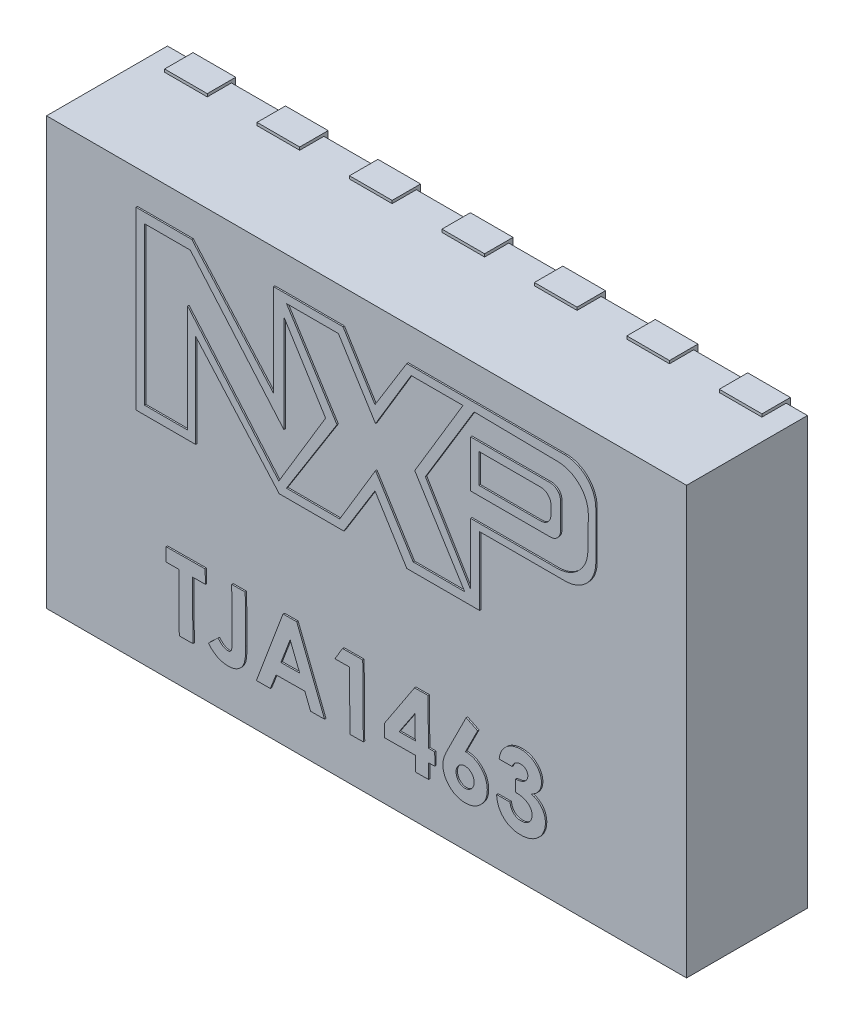
SolidWorks part; units mm, degrees
ref_plane "Front Plane" through (0, 0, 0) normal (0, 0, 1) x (1, 0, 0)
ref_plane "Top Plane" through (0, 0, 0) normal (0, 1, 0) x (1, 0, 0)
ref_plane "Right Plane" through (0, 0, 0) normal (1, 0, 0) x (0, 0, -1)
sketch "Sketch1" plane through (0, 0, 0) normal (0, 0, 1) x (1, 0, 0)
  line L1 (2.25, 1.5) -> (-2.25, 1.5)
  line L2 (2.25, 1.5) -> (2.25, -1.5)
  line L3 (2.25, -1.5) -> (-2.25, -1.5)
  line L4 (-2.25, 1.5) -> (-2.25, -1.5)
  line L5 (2.25, 1.5) -> (-2.25, -1.5) construction
  line L6 (2.25, -1.5) -> (-2.25, 1.5) construction
  point P0 (0, 0)
  dimension "D1" = 4.5
  dimension "D2" = 3
extrude "Boss-Extrude1" add sketch "Sketch1" along normal blind 0.85
sketch "Sketch2" plane through (0, 0, 0) normal (0, 0, -1) x (-1, 0, 0)
  line L0 (-2.25, 1.5) -> (2.25, 1.5) construction
  line L1 (2.1, 0.8) -> (-2.1, 0.8)
  line L2 (2.1, 0.8) -> (2.1, -0.8)
  line L3 (2.1, -0.8) -> (-2.1, -0.8)
  line L4 (-2.1, 0.8) -> (-2.1, -0.8)
  line L5 (2.1, 0.8) -> (-2.1, -0.8) construction
  line L6 (2.1, -0.8) -> (-2.1, 0.8) construction
  line L7 (-2.1, 1.6573) -> (-1.8, 1.6573)
  line L8 (-2.1, 1.6573) -> (-2.1, 1.1)
  line L9 (-2.1, 1.1) -> (-1.8, 1.1)
  line L10 (-1.8, 1.6573) -> (-1.8, 1.1)
  line L11 (-1.45, 1.6573) -> (-1.45, 1.1)
  line L12 (-1.45, 1.6573) -> (-1.15, 1.6573)
  line L13 (-1.15, 1.6573) -> (-1.15, 1.1)
  line L14 (-1.45, 1.1) -> (-1.15, 1.1)
  line L15 (-0.8, 1.6573) -> (-0.8, 1.1)
  line L16 (-0.8, 1.6573) -> (-0.5, 1.6573)
  line L17 (-0.5, 1.6573) -> (-0.5, 1.1)
  line L18 (-0.8, 1.1) -> (-0.5, 1.1)
  line L19 (-0.15, 1.6573) -> (-0.15, 1.1)
  line L20 (-0.15, 1.6573) -> (0.15, 1.6573)
  line L21 (0.15, 1.6573) -> (0.15, 1.1)
  line L22 (-0.15, 1.1) -> (0.15, 1.1)
  line L23 (0.5, 1.6573) -> (0.5, 1.1)
  line L24 (0.5, 1.6573) -> (0.8, 1.6573)
  line L25 (0.8, 1.6573) -> (0.8, 1.1)
  line L26 (0.5, 1.1) -> (0.8, 1.1)
  line L27 (1.15, 1.6573) -> (1.15, 1.1)
  line L28 (1.15, 1.6573) -> (1.45, 1.6573)
  line L29 (1.45, 1.6573) -> (1.45, 1.1)
  line L30 (1.15, 1.1) -> (1.45, 1.1)
  line L31 (1.8, 1.6573) -> (1.8, 1.1)
  line L32 (1.8, 1.6573) -> (2.1, 1.6573)
  line L33 (2.1, 1.6573) -> (2.1, 1.1)
  line L34 (1.8, 1.1) -> (2.1, 1.1)
  line L35 (0, 0) -> (1.2289, 0) construction
  line L36 (1.8, -1.1) -> (2.1, -1.1)
  line L37 (2.1, -1.6573) -> (2.1, -1.1)
  line L38 (1.8, -1.6573) -> (2.1, -1.6573)
  line L39 (1.8, -1.6573) -> (1.8, -1.1)
  line L40 (1.15, -1.1) -> (1.45, -1.1)
  line L41 (1.45, -1.6573) -> (1.45, -1.1)
  line L42 (1.15, -1.6573) -> (1.45, -1.6573)
  line L43 (1.15, -1.6573) -> (1.15, -1.1)
  line L44 (0.5, -1.1) -> (0.8, -1.1)
  line L45 (0.8, -1.6573) -> (0.8, -1.1)
  line L46 (0.5, -1.6573) -> (0.8, -1.6573)
  line L47 (0.5, -1.6573) -> (0.5, -1.1)
  line L48 (-0.15, -1.1) -> (0.15, -1.1)
  line L49 (0.15, -1.6573) -> (0.15, -1.1)
  line L50 (-0.15, -1.6573) -> (0.15, -1.6573)
  line L51 (-0.15, -1.6573) -> (-0.15, -1.1)
  line L52 (-0.8, -1.1) -> (-0.5, -1.1)
  line L53 (-0.5, -1.6573) -> (-0.5, -1.1)
  line L54 (-0.8, -1.6573) -> (-0.5, -1.6573)
  line L55 (-0.8, -1.6573) -> (-0.8, -1.1)
  line L56 (-1.45, -1.1) -> (-1.15, -1.1)
  line L57 (-1.15, -1.6573) -> (-1.15, -1.1)
  line L58 (-1.45, -1.6573) -> (-1.15, -1.6573)
  line L59 (-1.45, -1.6573) -> (-1.45, -1.1)
  line L60 (-1.8, -1.6573) -> (-1.8, -1.1)
  line L61 (-2.1, -1.1) -> (-1.8, -1.1)
  line L62 (-2.1, -1.6573) -> (-2.1, -1.1)
  line L63 (-2.1, -1.6573) -> (-1.8, -1.6573)
  point P0 (0, 0)
  dimension "D1" = 1.6
  dimension "D2" = 4.2
  dimension "D3" = 0.4
  dimension "D4" = 0.3
  dimension "D5" = 7
extrude "Boss-Extrude2" add sketch "Sketch2" along normal blind 0.03
sketch "Sketch3" plane through (0, 0, 0.85) normal (0, 0, 1) x (1, 0, 0)
  line L1 (-2.25, 1.5) -> (3.2924, 1.5)
  line L2 (-2.25, 1.5) -> (-2.25, 1.9025)
  line L3 (-2.25, 1.9025) -> (3.2924, 1.9025)
  line L4 (3.2924, 1.5) -> (3.2924, 1.9025)
  line L5 (-2.25, -1.5) -> (2.8586, -1.5)
  line L6 (-2.25, -1.5) -> (-2.25, -2.0374)
  line L7 (-2.25, -2.0374) -> (2.8586, -2.0374)
  line L8 (2.8586, -1.5) -> (2.8586, -2.0374)
extrude "Cut-Extrude1" cut sketch "Sketch3" against normal blind 2.03
sketch "Sketch4" plane through (0, -1.5, 0) normal (0, -1, 0) x (1, 0, 0)
  line L0 (-1.8, 0) -> (-1.8, -0.03) construction
  line L1 (-2.1, -0.03) -> (-1.8, -0.03)
  line L2 (-2.1, -0.03) -> (-2.1, 0.17)
  line L3 (-2.1, 0.17) -> (-1.8, 0.17)
  line L4 (-1.8, -0.03) -> (-1.8, 0.17)
  line L5 (-1.45, -0.03) -> (-1.45, 0.17)
  line L6 (-1.45, -0.03) -> (-1.15, -0.03)
  line L7 (-1.15, -0.03) -> (-1.15, 0.17)
  line L8 (-1.45, 0.17) -> (-1.15, 0.17)
  line L9 (-0.8, -0.03) -> (-0.8, 0.17)
  line L10 (-0.8, -0.03) -> (-0.5, -0.03)
  line L11 (-0.5, -0.03) -> (-0.5, 0.17)
  line L12 (-0.8, 0.17) -> (-0.5, 0.17)
  line L13 (-0.15, -0.03) -> (-0.15, 0.17)
  line L14 (-0.15, -0.03) -> (0.15, -0.03)
  line L15 (0.15, -0.03) -> (0.15, 0.17)
  line L16 (-0.15, 0.17) -> (0.15, 0.17)
  line L17 (0.5, -0.03) -> (0.5, 0.17)
  line L18 (0.5, -0.03) -> (0.8, -0.03)
  line L19 (0.8, -0.03) -> (0.8, 0.17)
  line L20 (0.5, 0.17) -> (0.8, 0.17)
  line L21 (1.15, -0.03) -> (1.15, 0.17)
  line L22 (1.15, -0.03) -> (1.45, -0.03)
  line L23 (1.45, -0.03) -> (1.45, 0.17)
  line L24 (1.15, 0.17) -> (1.45, 0.17)
  line L25 (1.8, -0.03) -> (1.8, 0.17)
  line L26 (1.8, -0.03) -> (2.1, -0.03)
  line L27 (2.1, -0.03) -> (2.1, 0.17)
  line L28 (1.8, 0.17) -> (2.1, 0.17)
  dimension "D1" = 0
  dimension "D2" = 0.2
  dimension "D3" = 7
extrude "Boss-Extrude3" add sketch "Sketch4" along normal blind 0.02
mirror "Mirror1" about plane through (0, 0, 0) normal (0, 1, 0) of "Boss-Extrude3"
sketch "Sketch8" plane through (0, 0, 0.85) normal (0, 0, 1) x (1, 0, 0)
  line L0 (70.666, 256.4211) -> (518.666, 256.4211) construction
  line L1 (-1.2186, 1.2679) -> (-0.6447, 0.6189)
  line L2 (-0.5532, 1.2103) -> (-0.188, 1.2103)
  line L3 (0.6998, 0.0824) -> (0.3376, 0.0824)
  line L4 (-0.6447, 1.2679) -> (-0.1555, 1.2679)
  line L5 (-1.1921, 0.6918) -> (-1.1921, 0.0329)
  line L6 (-0.188, 1.2103) -> (0.0731, 0.7923)
  line L7 (-0.1497, 0.0266) -> (-0.6039, 0.0266)
  line L8 (-1.1921, 0.0329) -> (-1.6111, 0.0329)
  line L9 (0.7662, 1.2103) -> (1.3564, 1.202)
  line L10 (0.742, 1.046) -> (0.742, 0.7163)
  line L11 (1.4057, 0.5003) -> (0.8054, 0.5003)
  line L12 (-1.552, 0.0924) -> (-1.552, 1.1975)
  line L13 (0.7998, 0.9863) -> (1.2343, 0.9863)
  line L14 (1.5693, 0.983) -> (1.5662, 0.7627)
  line L15 (1.3063, 0.9143) -> (1.3063, 0.852)
  line L16 (-1.6111, 0.0329) -> (-1.6111, 1.2679)
  line L17 (0.8054, 0.0202) -> (0.293, 0.0202)
  line L18 (-0.1981, 0.65) -> (-0.5532, 1.2103)
  line L19 (0.742, 0.5497) -> (0.742, 0.1156)
  line L20 (0.293, 1.2679) -> (1.4057, 1.2679)
  line L21 (-0.5714, 0.4334) -> (-0.5714, 1.1203)
  line L22 (0.3488, 0.6442) -> (0.6998, 0.0824)
  line L23 (0.293, 0.0202) -> (0.0692, 0.381)
  line L24 (-0.6069, 0.1027) -> (-1.248, 0.8474)
  line L25 (0.4233, 0.6442) -> (0.7662, 1.2103)
  line L26 (1.3016, 0.7163) -> (0.742, 0.7163)
  line L27 (1.6217, 1.0519) -> (1.6217, 0.7163)
  line L28 (-0.6039, 0.0266) -> (-1.1921, 0.6918)
  line L29 (0.0731, 0.5059) -> (-0.1786, 0.086)
  line L30 (0.0692, 0.9056) -> (0.293, 1.2679)
  line L31 (0.0731, 0.7923) -> (0.3236, 1.2103)
  line L32 (-0.5532, 0.086) -> (-0.1981, 0.65)
  line L33 (-0.5714, 1.1203) -> (-0.278, 0.65)
  line L34 (0.3236, 1.2103) -> (0.6882, 1.2103)
  line L35 (0.7998, 0.9863) -> (0.7998, 0.78)
  line L36 (-0.1786, 0.086) -> (-0.5532, 0.086)
  line L37 (0.7998, 0.78) -> (1.2343, 0.78)
  line L38 (0.3376, 0.0824) -> (0.0731, 0.5059)
  line L39 (0.742, 1.046) -> (1.3016, 1.046)
  line L40 (0.8054, 0.5003) -> (0.8054, 0.0202)
  line L41 (-1.2291, 1.1975) -> (-0.5714, 0.4334)
  line L42 (1.3736, 0.974) -> (1.3736, 0.7883)
  line L43 (-0.1555, 1.2679) -> (0.0692, 0.9056)
  line L44 (0.0692, 0.381) -> (-0.1497, 0.0266)
  line L45 (-1.248, 0.0924) -> (-1.552, 0.0924)
  line L46 (1.3503, 0.5497) -> (0.742, 0.5497)
  line L47 (-1.6111, 1.2679) -> (-1.2186, 1.2679)
  line L48 (-0.278, 0.65) -> (-0.6069, 0.1027)
  line L49 (0.6882, 1.2103) -> (0.3488, 0.6442)
  line L50 (-0.6447, 0.6189) -> (-0.6447, 1.2679)
  line L51 (-1.552, 1.1975) -> (-1.2291, 1.1975)
  line L52 (-1.248, 0.8474) -> (-1.248, 0.0924)
  line L53 (0.742, 0.1156) -> (0.4233, 0.6442)
  line L54 (-1.6111, -1.125) -> (1.3503, -1.125) construction
  arc A0 (1.3016, 1.046) -> (1.3736, 0.974) centre (1.3016, 0.974) cw
  arc A1 (1.4057, 1.2679) -> (1.6217, 1.0519) centre (1.4057, 1.0519) cw
  arc A2 (1.3736, 0.7883) -> (1.3016, 0.7163) centre (1.3016, 0.7883) cw
  arc A3 (1.6217, 0.7163) -> (1.4057, 0.5003) centre (1.4057, 0.7163) cw
  arc A4 (1.2343, 0.9863) -> (1.3063, 0.9143) centre (1.2343, 0.9143) cw
  arc A5 (1.5662, 0.7627) -> (1.3503, 0.5497) centre (1.3503, 0.7657) cw
  arc A6 (1.2343, 0.78) -> (1.3063, 0.852) centre (1.2343, 0.852) ccw
  arc A7 (1.3564, 1.202) -> (1.5693, 0.983) centre (1.3533, 0.9861) cw
  text T0 "<b>TJA1145A</b>" font "Century Gothic" height 0.5
extrude "Boss-Extrude4" add sketch "Sketch8" along normal blind 0.01 contours A3 L27 A1 L20 L30 L43 L4 L50 L1 L47 L16 L8 L5 L28 L7 L44 L23 L17 L40 L11 L34 L49 L22 L3 L38 L29 L36 L32 L18 L2 L6 L31 L24 L52 L45 L12 L51 L41 L21 L33 L48 L9 A7 L14 A5 L46 L19 L53 | A2 L42 A0 L39 L10 L26 A6 L37 L35 L13 A4 L15
sketch "Sketch9" plane through (0, 0, 0.85) normal (0, 0, 1) x (1, 0, 0)
  line L0 (-1.4028, -1.1911) -> (1.6601, -1.1911) construction
  text T0 "<b>TJA1463</b>" font "Century Gothic" height 0.5
  point P3 (-1.4028, -1.1911)
extrude "Boss-Extrude5" add sketch "Sketch9" along normal blind 0.01
